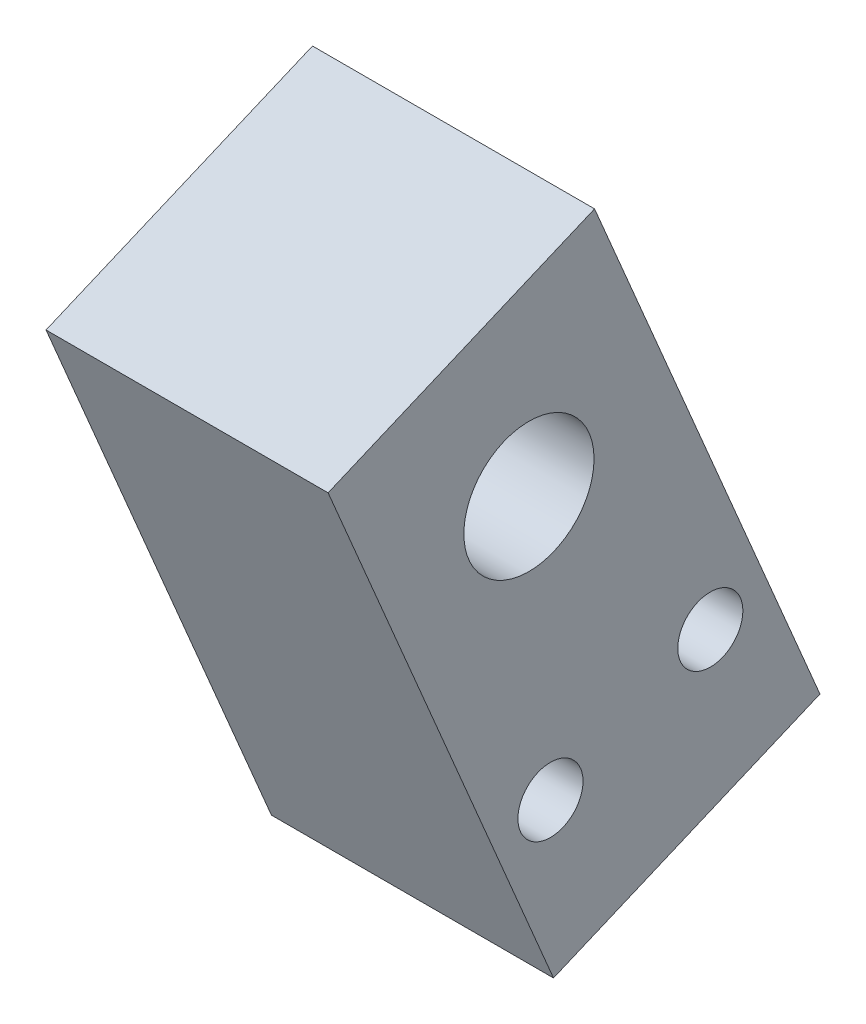
SolidWorks part; units mm, degrees
ref_plane "Front Plane" through (0, 0, 0) normal (0, 0, 1) x (1, 0, 0)
ref_plane "Top Plane" through (0, 0, 0) normal (0, 1, 0) x (1, 0, 0)
ref_plane "Right Plane" through (0, 0, 0) normal (1, 0, 0) x (0, 0, -1)
sketch "Sketch2" plane through (0, 0.5403, -1.2775) normal (0, 0.3896, -0.921) x (-1, 0, 0)
  line L0 (21.3771, -28.276) -> (21.3771, -39.276) construction
  line L1 (1.8771, 6.824) -> (21.3771, 6.824)
  line L2 (1.8771, 6.824) -> (1.8771, -33.176)
  line L3 (1.8771, -33.176) -> (21.3771, -33.176)
  line L4 (21.3771, 6.824) -> (21.3771, -33.176)
  line L5 (1.8771, -33.176) -> (1.8771, 6.824) construction
extrude "Boss-Extrude1" add sketch "Sketch2" against normal blind 20
sketch "Sketch3" plane through (-1.8771, 0, 0) normal (1, 0, 0) x (0, 0, -1)
  circle A0 centre (-5.9161, -8.1224) radius 4.5
  dimension "D1" = 9
extrude "M10 threaded - 9mm-thru" cut sketch "Sketch3" against normal through all
sketch "Sketch4" plane through (-1.8771, 0, 0) normal (1, 0, 0) x (0, 0, -1)
  circle A0 centre (6.6221, -22.3629) radius 2.25
  circle A1 centre (-4.4299, -27.0378) radius 2.25
  dimension "D1" = 4.5
  dimension "D2" = 4.5
extrude "M4 clearance - 4.5mm - thru" cut sketch "Sketch4" against normal through all
